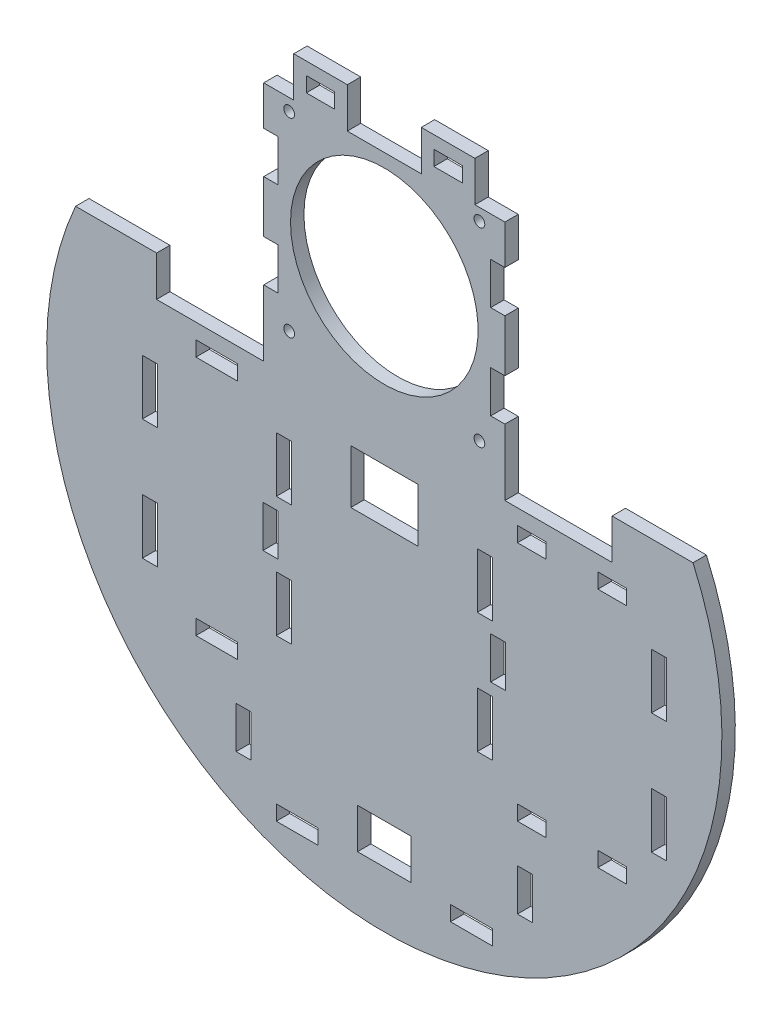
SolidWorks part; units mm, degrees
ref_plane "Спереди" through (0, 0, 0) normal (0, 0, 1) x (1, 0, 0)
ref_plane "Сверху" through (0, 0, 0) normal (0, 1, 0) x (1, 0, 0)
ref_plane "Справа" through (0, 0, 0) normal (1, 0, 0) x (0, 0, -1)
sketch "Sketch1" plane through (0, 0, 0) normal (0, 0, -1) x (-1, 0, 0)
  line L0 (-70.4767, 23.967) -> (-70.4767, -147.0162) construction
  line L1 (-25.4767, 28.967) -> (-36.6767, 28.967)
  line L4 (-56.6767, 28.967) -> (-84.2767, 28.967)
  line L5 (-155.4767, -46.033) -> (-185.6939, -46.033)
  line L6 (-104.2767, 28.967) -> (-115.4767, 28.967)
  line L11 (14.5233, -46.033) -> (44.7405, -46.033)
  line L24 (-95.4767, -122.033) -> (-45.4767, -72.033) construction
  line L25 (-95.4767, -72.033) -> (-45.4767, -122.033) construction
  line L86 (-84.2767, 28.967) -> (-84.2767, 43.967)
  line L140 (-36.6767, 28.967) -> (-36.6767, 43.967)
  line L141 (-36.6767, 43.967) -> (-56.6767, 43.967)
  line L142 (-56.6767, 28.967) -> (-56.6767, 43.967)
  line L143 (-104.2767, 43.967) -> (-84.2767, 43.967)
  line L144 (-104.2767, 28.967) -> (-104.2767, 43.967)
  line L153 (-25.4767, 28.967) -> (-25.4767, 14.267)
  line L154 (-60.4767, -202.033) -> (-80.4767, -202.033)
  line L155 (-60.4767, -202.033) -> (-60.4767, -187.033)
  line L156 (-60.4767, -187.033) -> (-80.4767, -187.033)
  line L157 (-80.4767, -202.033) -> (-80.4767, -187.033)
  line L158 (-25.4767, -61.033) -> (14.5233, -61.033)
  line L159 (14.5233, -61.033) -> (14.5233, -46.033)
  line L160 (-155.4767, -61.033) -> (-155.4767, -46.033)
  line L161 (-115.4767, -61.033) -> (-155.4767, -61.033)
  line L162 (-115.4767, 28.967) -> (-115.4767, 14.267)
  line L163 (-75.4605, -11.033) -> (-62.9522, -11.033) construction
  line L180 (-25.4767, -1.333) -> (-25.4767, -20.733)
  line L181 (-25.4767, -36.333) -> (-25.4767, -61.033)
  line L182 (-115.4767, -36.333) -> (-115.4767, -61.033)
  line L183 (-115.4767, -1.333) -> (-115.4767, -20.733)
  line L200 (-25.4767, 14.267) -> (-30.7767, 14.267)
  line L201 (-57.9767, -72.033) -> (-82.9767, -72.033)
  line L202 (-57.9767, -72.033) -> (-57.9767, -92.033)
  line L203 (-57.9767, -92.033) -> (-82.9767, -92.033)
  line L204 (-82.9767, -72.033) -> (-82.9767, -92.033)
  line L205 (-30.7767, 14.267) -> (-30.7767, -1.333)
  line L206 (-25.4767, -1.333) -> (-30.7767, -1.333)
  line L207 (-25.4767, -20.733) -> (-30.7767, -20.733)
  line L208 (-30.7767, -36.333) -> (-30.7767, -20.733)
  line L209 (-25.4767, -36.333) -> (-30.7767, -36.333)
  line L210 (-115.4767, -36.333) -> (-110.1767, -36.333)
  line L211 (-110.1767, -36.333) -> (-110.1767, -20.733)
  line L212 (-115.4767, -20.733) -> (-110.1767, -20.733)
  line L213 (-115.4767, -1.333) -> (-110.1767, -1.333)
  line L214 (-110.1767, 14.267) -> (-110.1767, -1.333)
  line L215 (-115.4767, 14.267) -> (-110.1767, 14.267)
  line L216 (-41.3767, 33.667) -> (-41.3767, 39.267)
  line L217 (-41.3767, 39.267) -> (-51.9767, 39.267)
  line L218 (-51.9767, 33.667) -> (-51.9767, 39.267)
  line L219 (-41.3767, 33.667) -> (-51.9767, 33.667)
  line L220 (-99.5767, 39.267) -> (-88.9767, 39.267)
  line L221 (-88.9767, 33.667) -> (-88.9767, 39.267)
  line L222 (-99.5767, 33.667) -> (-88.9767, 33.667)
  line L223 (-99.5767, 33.667) -> (-99.5767, 39.267)
  line L224 (-15.7767, -72.333) -> (-15.7767, -66.733)
  line L225 (-15.7767, -66.733) -> (-0.1767, -66.733)
  line L226 (-0.1767, -72.333) -> (-0.1767, -66.733)
  line L227 (-15.7767, -72.333) -> (-0.1767, -72.333)
  line L228 (19.8233, -81.733) -> (19.8233, -102.333)
  line L229 (19.8233, -102.333) -> (14.2233, -102.333)
  line L230 (14.2233, -81.733) -> (14.2233, -102.333)
  line L231 (19.8233, -81.733) -> (14.2233, -81.733)
  line L232 (-30.1767, -81.733) -> (-30.1767, -102.333)
  line L233 (-30.1767, -102.333) -> (-35.7767, -102.333)
  line L234 (-35.7767, -81.733) -> (-35.7767, -102.333)
  line L235 (-30.1767, -81.733) -> (-35.7767, -81.733)
  line L236 (-30.7767, -106.733) -> (-30.7767, -122.333)
  line L237 (-30.7767, -122.333) -> (-25.1767, -122.333)
  line L238 (-25.1767, -106.733) -> (-25.1767, -122.333)
  line L239 (-30.7767, -106.733) -> (-25.1767, -106.733)
  line L240 (19.8233, -126.733) -> (19.8233, -147.333)
  line L241 (19.8233, -147.333) -> (14.2233, -147.333)
  line L242 (14.2233, -126.733) -> (14.2233, -147.333)
  line L243 (19.8233, -126.733) -> (14.2233, -126.733)
  line L244 (-15.7767, -162.333) -> (-15.7767, -156.733)
  line L245 (-15.7767, -156.733) -> (-0.1767, -156.733)
  line L246 (-0.1767, -162.333) -> (-0.1767, -156.733)
  line L247 (-15.7767, -162.333) -> (-0.1767, -162.333)
  line L248 (-30.1767, -126.733) -> (-30.1767, -147.333)
  line L249 (-30.1767, -147.333) -> (-35.7767, -147.333)
  line L250 (-35.7767, -126.733) -> (-35.7767, -147.333)
  line L251 (-30.1767, -126.733) -> (-35.7767, -126.733)
  line L252 (-15.1767, -192.333) -> (-20.7767, -192.333)
  line L253 (-20.7767, -176.733) -> (-20.7767, -192.333)
  line L254 (-15.1767, -176.733) -> (-20.7767, -176.733)
  line L255 (-15.1767, -176.733) -> (-15.1767, -192.333)
  line L256 (-30.1767, -207.333) -> (-45.7767, -207.333)
  line L257 (-45.7767, -201.733) -> (-45.7767, -207.333)
  line L258 (-30.1767, -201.733) -> (-45.7767, -201.733)
  line L259 (-30.1767, -201.733) -> (-30.1767, -207.333)
  line L260 (-110.7767, -201.733) -> (-110.7767, -207.333)
  line L261 (-110.7767, -207.333) -> (-95.1767, -207.333)
  line L262 (-95.1767, -201.733) -> (-95.1767, -207.333)
  line L263 (-110.7767, -201.733) -> (-95.1767, -201.733)
  line L264 (-125.7767, -176.733) -> (-125.7767, -192.333)
  line L265 (-125.7767, -192.333) -> (-120.1767, -192.333)
  line L266 (-120.1767, -176.733) -> (-120.1767, -192.333)
  line L267 (-125.7767, -176.733) -> (-120.1767, -176.733)
  line L268 (-130.7767, -162.333) -> (-130.7767, -156.733)
  line L269 (-130.7767, -156.733) -> (-120.1767, -156.733)
  line L270 (-120.1767, -162.333) -> (-120.1767, -156.733)
  line L271 (-130.7767, -162.333) -> (-120.1767, -162.333)
  line L272 (-160.7767, -162.333) -> (-160.7767, -156.733)
  line L273 (-160.7767, -156.733) -> (-150.1767, -156.733)
  line L274 (-150.1767, -162.333) -> (-150.1767, -156.733)
  line L275 (-160.7767, -162.333) -> (-150.1767, -162.333)
  line L276 (-105.1767, -126.733) -> (-105.1767, -147.333)
  line L277 (-105.1767, -147.333) -> (-110.7767, -147.333)
  line L278 (-110.7767, -126.733) -> (-110.7767, -147.333)
  line L279 (-105.1767, -126.733) -> (-110.7767, -126.733)
  line L280 (-170.1767, -126.733) -> (-170.1767, -147.333)
  line L281 (-170.1767, -147.333) -> (-175.7767, -147.333)
  line L282 (-175.7767, -126.733) -> (-175.7767, -147.333)
  line L283 (-170.1767, -126.733) -> (-175.7767, -126.733)
  line L284 (-110.1767, -122.333) -> (-115.7767, -122.333)
  line L285 (-115.7767, -106.733) -> (-115.7767, -122.333)
  line L286 (-110.1767, -106.733) -> (-115.7767, -106.733)
  line L287 (-110.1767, -106.733) -> (-110.1767, -122.333)
  line L288 (-105.1767, -81.733) -> (-105.1767, -102.333)
  line L289 (-105.1767, -102.333) -> (-110.7767, -102.333)
  line L290 (-110.7767, -81.733) -> (-110.7767, -102.333)
  line L291 (-105.1767, -81.733) -> (-110.7767, -81.733)
  line L292 (-170.1767, -81.733) -> (-170.1767, -102.333)
  line L293 (-170.1767, -102.333) -> (-175.7767, -102.333)
  line L294 (-175.7767, -81.733) -> (-175.7767, -102.333)
  line L295 (-170.1767, -81.733) -> (-175.7767, -81.733)
  line L296 (-130.7767, -72.333) -> (-130.7767, -66.733)
  line L297 (-130.7767, -66.733) -> (-120.1767, -66.733)
  line L298 (-120.1767, -72.333) -> (-120.1767, -66.733)
  line L299 (-130.7767, -72.333) -> (-120.1767, -72.333)
  line L300 (-160.7767, -72.333) -> (-160.7767, -66.733)
  line L301 (-160.7767, -66.733) -> (-150.1767, -66.733)
  line L302 (-150.1767, -72.333) -> (-150.1767, -66.733)
  line L303 (-160.7767, -72.333) -> (-150.1767, -72.333)
  arc A0 (-185.6939, -46.033) -> (44.7405, -46.033) centre (-70.4767, -97.033) ccw
  circle A1 centre (-70.4767, -11.033) radius 35
  circle A2 centre (-34.9767, 24.467) radius 2
  circle A3 centre (-105.9767, 24.467) radius 2
  circle A4 centre (-105.9767, -46.533) radius 2
  circle A5 centre (-34.9767, -46.533) radius 2
  point P20 (-70.4767, -97.033)
  dimension "D11" = 70
  dimension "D5" = 20
  dimension "D9" = 50
  dimension "D10" = 50
  dimension "D33" = 15
  dimension "D34" = 25
  dimension "D38" = 15
  dimension "D39" = 20
  dimension "D41" = 90
  dimension "D42" = 20
  dimension "D43" = 12.5
extrude "Boss-Extrude1" add sketch "Sketch1" along normal blind 5
